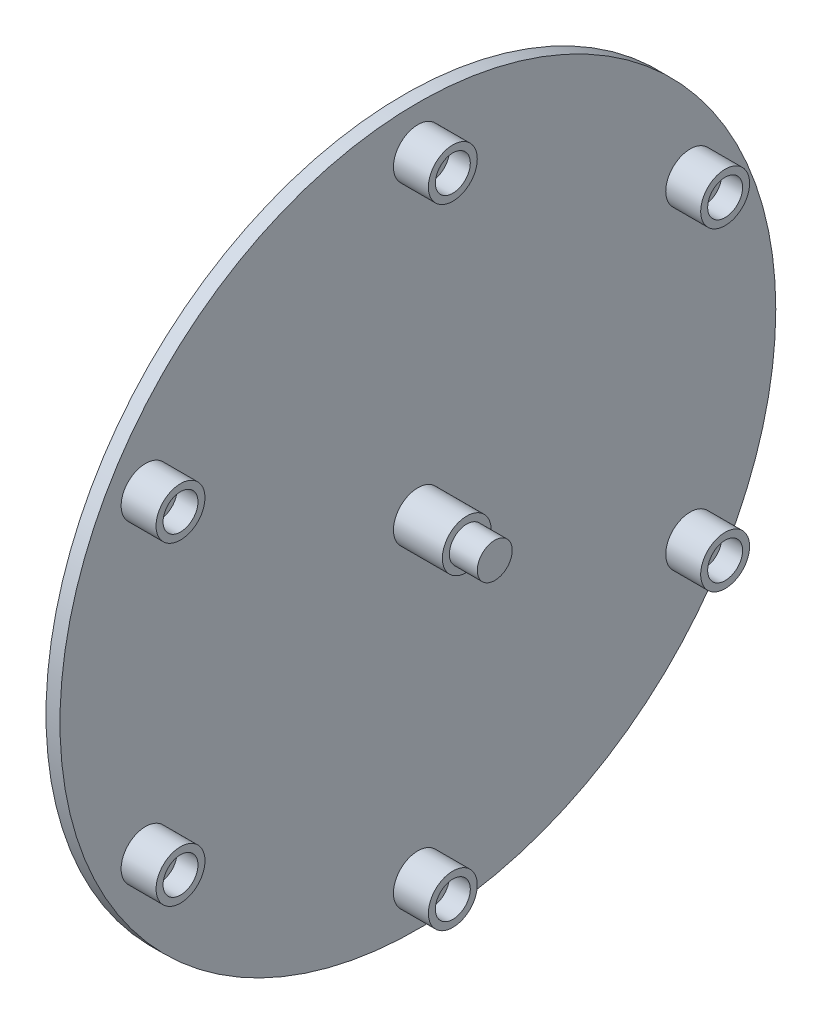
SolidWorks part; units mm, degrees
ref_plane "前视基准面" through (0, 0, 0) normal (0, 0, 1) x (1, 0, 0)
ref_plane "上视基准面" through (0, 0, 0) normal (0, 1, 0) x (1, 0, 0)
ref_plane "右视基准面" through (0, 0, 0) normal (1, 0, 0) x (0, 0, -1)
other "Configuration Table"
sketch "草图1" plane through (0, 0, 0) normal (1, 0, 0) x (0, 0, -1)
  circle A0 centre (0, 0) radius 51.2209
extrude "凸台-拉伸1" add sketch "草图1" along normal blind 2
sketch "草图2" plane through (2, 0, 0) normal (1, 0, 0) x (0, 0, -1)
  circle A0 centre (0, 45) radius 3.5
  dimension "D1" = 7
  dimension "D2" = 45
extrude "凸台-拉伸2" add sketch "草图2" along normal blind 5 contours A0
pattern_circular "阵列(圆周)1" count 6 over 360 about axis through (0, 0, 0) along (1, 0, 0) of "凸台-拉伸2"
sketch "草图3" plane through (7, 0, 0) normal (1, 0, 0) x (0, 0, -1)
  circle A0 centre (0, 45) radius 2.5
  dimension "D1" = 5
extrude "切除-拉伸1" cut sketch "草图3" against normal blind 3
pattern_circular "阵列(圆周)2" count 6 over 360 about axis through (0, 0, 0) along (1, 0, 0) of "切除-拉伸1"
sketch "草图4" plane through (2, 0, 0) normal (1, 0, 0) x (0, 0, -1)
  circle A0 centre (0, 0) radius 2.5
  dimension "D1" = 5
extrude "凸台-拉伸3" add sketch "草图4" along normal blind 11
sketch "草图5" plane through (2, 0, 0) normal (1, 0, 0) x (0, 0, -1)
  circle A2 centre (0, 0) radius 3.5
  circle A3 centre (0, 0) radius 3.5
  dimension "D1" = 1
extrude "凸台-拉伸4" add sketch "草图5" along normal blind 7
sketch "草图6" plane through (0, 0, 0) normal (-1, 0, 0) x (0, 0, 1)
  circle A0 centre (0, 0) radius 5
  dimension "D1" = 10
extrude "凸台-拉伸5" add sketch "草图6" along normal blind 20 contours A0
sketch "草图7" plane through (0, 0, 0) normal (-1, 0, 0) x (0, 0, 1)
  circle A2 centre (0, 0) radius 6
  circle A3 centre (0, 0) radius 6
  dimension "D1" = 1
extrude "凸台-拉伸6" add sketch "草图7" along normal blind 5
sketch "草图8" plane through (-20, 0, 0) normal (-1, 0, 0) x (0, 0, 1)
  circle A0 centre (0, 0) radius 2.5
  dimension "D1" = 5
extrude "切除-拉伸2" cut sketch "草图8" against normal blind 7
